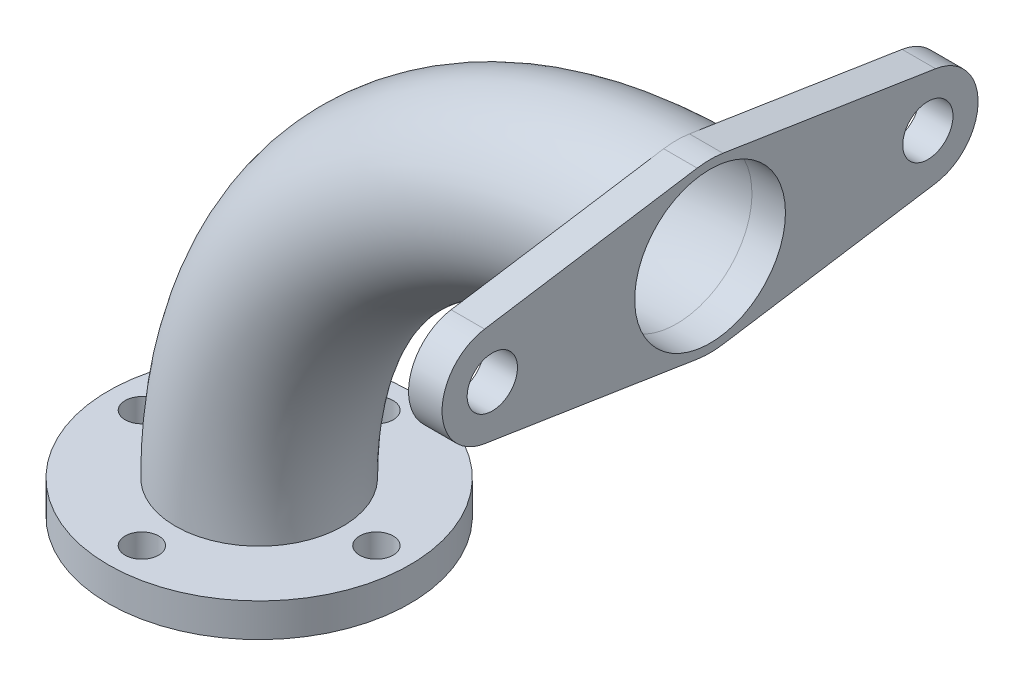
SolidWorks part; units mm, degrees
ref_plane "Front Plane" through (0, 0, 0) normal (0, 0, 1) x (1, 0, 0)
ref_plane "Top Plane" through (0, 0, 0) normal (0, 1, 0) x (1, 0, 0)
ref_plane "Right Plane" through (0, 0, 0) normal (1, 0, 0) x (0, 0, -1)
sketch "Sketch1" plane through (0, 0, 0) normal (0, 1, 0) x (1, 0, 0)
  circle A0 centre (0, 0) radius 45
  circle A1 centre (0, 0) radius 35 construction
  circle A2 centre (0, 35) radius 5
  circle A3 centre (35, 0) radius 5
  circle A4 centre (0, -35) radius 5
  circle A5 centre (-35, 0) radius 5
  circle A6 centre (0, 0) radius 22.5
  point P15 (0, 0)
  dimension "D1" = 90
  dimension "D2" = 70
  dimension "D3" = 10
  dimension "D5" = 45
  dimension "D4" = 4
extrude "Boss-Extrude1" add sketch "Sketch1" along normal blind 10
sketch "Sketch2" plane through (0, 0, 0) normal (0, 0, 1) x (1, 0, 0)
  line L0 (5, 10) -> (-5, 10) construction
  line L1 (-0.4006, 10) -> (124.5994, 10) construction
  line L3 (124.5994, 135) -> (124.5994, 10) construction
  arc A1 (124.5994, 135) -> (-0.4006, 10) centre (124.5994, 10) ccw
  dimension "D1" = 250
sketch "Sketch3" plane through (0, 10, 0) normal (0, 1, 0) x (1, 0, 0)
  circle A0 centre (0, 0) radius 22.5
  circle A1 centre (0, 0) radius 25
  circle A2 centre (0, 0) radius 45 construction
  point P4 (-4.0241, 2.0548)
  point P5 (0, 0)
  dimension "D1" = 45
  dimension "D2" = 50
sweep "Sweep1" add profiles "Sketch3" path "Sketch2"
sketch "Sketch4" plane through (124.5994, 0, 0) normal (1, 0, 0) x (0, 0, -1)
  line L0 (0, 134.5994) -> (-65, 134.5994) construction
  line L1 (-3.8462, 159.3017) -> (-67.3077, 149.4208)
  line L2 (-3.8462, 109.897) -> (-67.3077, 119.7779)
  line L3 (0, 134.5994) -> (0, 109.5994) construction
  line L4 (-3.8462, 159.3017) -> (-67.3077, 149.4208)
  line L5 (-3.8462, 109.897) -> (-67.3077, 119.7779)
  line L6 (3.8462, 159.3017) -> (67.3077, 149.4208)
  line L7 (3.8462, 109.897) -> (67.3077, 119.7779)
  circle A0 centre (-65, 134.5994) radius 7.5
  circle A1 centre (0, 134.5994) radius 25 construction
  arc A3 (-67.3077, 149.4208) -> (-67.3077, 119.7779) centre (-65, 134.5994) ccw
  arc A4 (-3.8462, 159.3017) -> (-3.8462, 109.897) centre (0, 134.5994) ccw
  circle A5 centre (65, 134.5994) radius 7.5
  arc A6 (67.3077, 149.4208) -> (67.3077, 119.7779) centre (65, 134.5994) cw
  arc A7 (3.8462, 109.897) -> (3.8462, 159.3017) centre (0, 134.5994) ccw
  circle A8 centre (0, 134.5994) radius 22.5 construction
  circle A9 centre (0, 134.5994) radius 25
  circle A10 centre (0, 134.5994) radius 25
  circle A11 centre (0, 134.5994) radius 22.5
  circle M5 centre (0, 134.5994) radius 22.5
  circle M6 centre (0, 134.5994) radius 25
  dimension "D1" = 65
  dimension "D2" = 15
  dimension "D3" = 30
  dimension "D4" = 0
extrude "Boss-Extrude6" add sketch "Sketch4" along normal blind 10 contours L1 A3 L2 A0 M6 | A6 L6 L7 A5 M6 | M6 M5
